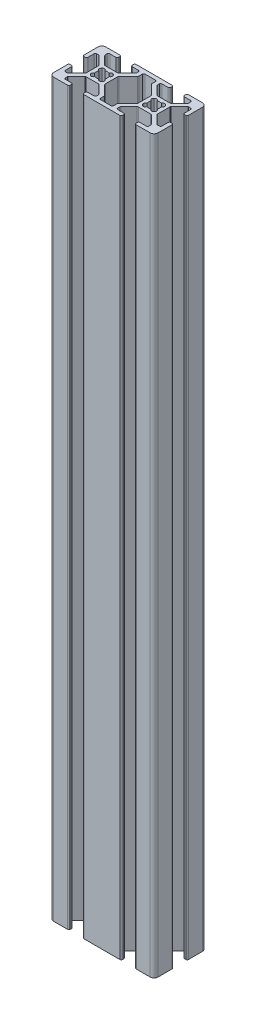
SolidWorks part; units mm, degrees
ref_plane "前视基准面" through (0, 0, 0) normal (0, 0, 1) x (1, 0, 0)
ref_plane "上视基准面" through (0, 0, 0) normal (0, 1, 0) x (1, 0, 0)
ref_plane "右视基准面" through (0, 0, 0) normal (1, 0, 0) x (0, 0, -1)
other "Configuration Table"
sketch "草图1" plane through (0, 0, 0) normal (0, 1, 0) x (1, 0, 0)
  line L0 (17.2471, 7.2074) -> (17.0675, 7.387)
  line L5 (17.0675, 11.6368) -> (17.2471, 11.8164)
  line L6 (21.4969, 11.8164) -> (21.6765, 11.6368)
  line L7 (21.6765, 7.387) -> (21.4969, 7.2074)
  line L8 (6.867, 1.5199) -> (6.867, 2.8671)
  line L9 (6.7182, 3.2263) -> (3.1758, 6.7687)
  line L10 (3.027, 7.128) -> (3.027, 11.8958)
  line L11 (3.1758, 12.255) -> (6.7182, 15.7974)
  line L26 (6.867, 16.1566) -> (6.867, 17.5039)
  line L41 (7.375, 18.0119) -> (11.369, 18.0119)
  line L56 (11.877, 17.5039) -> (11.877, 16.1566)
  line L71 (12.0258, 15.7974) -> (15.5682, 12.255)
  line L72 (15.717, 11.8958) -> (15.717, 7.128)
  line L73 (15.5682, 6.7687) -> (12.0258, 3.2263)
  line L74 (11.877, 2.8671) -> (11.877, 1.5199)
  line L75 (11.369, 1.0119) -> (7.375, 1.0119)
  line L76 (-2.7529, 7.2074) -> (-2.9325, 7.387)
  line L77 (-2.9325, 11.6368) -> (-2.7529, 11.8164)
  line L78 (1.4969, 11.8164) -> (1.6765, 11.6368)
  line L79 (1.6765, 7.387) -> (1.4969, 7.2074)
  line L80 (-3.0119, 5.8569) -> (1.7559, 5.8569)
  line L81 (2.1151, 5.7081) -> (5.2182, 2.605)
  line L82 (5.367, 2.2458) -> (5.367, 1.5199)
  line L83 (4.859, 1.0119) -> (2.51, 1.0119)
  line L84 (2.002, 0.5039) -> (2.002, 0.0199)
  line L85 (2.51, -0.4881) -> (16.234, -0.4881)
  line L86 (16.742, 0.0199) -> (16.742, 0.5039)
  line L87 (16.234, 1.0119) -> (13.885, 1.0119)
  line L88 (13.377, 1.5199) -> (13.377, 2.2458)
  line L89 (13.5258, 2.605) -> (16.6289, 5.7081)
  line L90 (16.9881, 5.8569) -> (21.7559, 5.8569)
  line L91 (22.1151, 5.7081) -> (25.2182, 2.605)
  line L92 (25.367, 2.2458) -> (25.367, 1.5199)
  line L93 (24.859, 1.0119) -> (22.51, 1.0119)
  line L94 (22.002, 0.5039) -> (22.002, 0.0199)
  line L95 (22.51, -0.4881) -> (27.872, -0.4881)
  line L96 (29.372, 1.0119) -> (29.372, 6.3739)
  line L97 (28.864, 6.8819) -> (28.38, 6.8819)
  line L98 (27.872, 6.3739) -> (27.872, 4.0249)
  line L99 (27.364, 3.5169) -> (26.6381, 3.5169)
  line L100 (26.2789, 3.6657) -> (23.1758, 6.7687)
  line L101 (23.027, 7.128) -> (23.027, 11.8958)
  line L102 (23.1758, 12.255) -> (26.2789, 15.3581)
  line L103 (26.6381, 15.5069) -> (27.364, 15.5069)
  line L104 (27.872, 14.9989) -> (27.872, 12.6499)
  line L105 (28.38, 12.1419) -> (28.864, 12.1419)
  line L106 (29.372, 12.6499) -> (29.372, 18.0119)
  line L107 (27.872, 19.5119) -> (22.51, 19.5119)
  line L108 (22.002, 19.0039) -> (22.002, 18.5199)
  line L109 (22.51, 18.0119) -> (24.859, 18.0119)
  line L110 (25.367, 17.5039) -> (25.367, 16.778)
  line L111 (25.2182, 16.4187) -> (22.1151, 13.3157)
  line L112 (21.7559, 13.1669) -> (16.9881, 13.1669)
  line L113 (16.6289, 13.3157) -> (13.5258, 16.4187)
  line L114 (13.377, 16.778) -> (13.377, 17.5039)
  line L115 (13.885, 18.0119) -> (16.234, 18.0119)
  line L116 (16.742, 18.5199) -> (16.742, 19.0039)
  line L117 (16.234, 19.5119) -> (2.51, 19.5119)
  line L118 (2.002, 19.0039) -> (2.002, 18.5199)
  line L119 (2.51, 18.0119) -> (4.859, 18.0119)
  line L120 (5.367, 17.5039) -> (5.367, 16.778)
  line L121 (5.2182, 16.4187) -> (2.1151, 13.3157)
  line L122 (1.7559, 13.1669) -> (-3.0119, 13.1669)
  line L123 (-3.3711, 13.3157) -> (-6.4742, 16.4187)
  line L124 (-6.623, 16.778) -> (-6.623, 17.5039)
  line L125 (-6.115, 18.0119) -> (-3.766, 18.0119)
  line L126 (-3.258, 18.5199) -> (-3.258, 19.0039)
  line L127 (-3.766, 19.5119) -> (-9.128, 19.5119)
  line L128 (-10.628, 18.0119) -> (-10.628, 12.6499)
  line L129 (-10.12, 12.1419) -> (-9.636, 12.1419)
  line L130 (-9.128, 12.6499) -> (-9.128, 14.9989)
  line L131 (-8.62, 15.5069) -> (-7.8941, 15.5069)
  line L132 (-7.5349, 15.3581) -> (-4.4318, 12.255)
  line L133 (-4.283, 11.8958) -> (-4.283, 7.128)
  line L134 (-4.4318, 6.7687) -> (-7.5349, 3.6657)
  line L135 (-7.8941, 3.5169) -> (-8.62, 3.5169)
  line L136 (-9.128, 4.0249) -> (-9.128, 6.3739)
  line L137 (-9.636, 6.8819) -> (-10.12, 6.8819)
  line L138 (-10.628, 6.3739) -> (-10.628, 1.0119)
  line L139 (-9.128, -0.4881) -> (-3.766, -0.4881)
  line L140 (-3.258, 0.0199) -> (-3.258, 0.5039)
  line L141 (-3.766, 1.0119) -> (-6.115, 1.0119)
  line L142 (-6.623, 1.5199) -> (-6.623, 2.2458)
  line L143 (-6.4742, 2.605) -> (-3.3711, 5.7081)
  arc A5 (17.4369, 8.7079) -> (17.0675, 7.387) centre (17.624, 7.9435) ccw
  arc A6 (17.4369, 10.3158) -> (17.4369, 8.7079) centre (19.372, 9.5119) ccw
  arc A7 (17.0675, 11.6368) -> (17.4369, 10.3158) centre (17.624, 11.0803) ccw
  arc A8 (18.568, 11.447) -> (17.2471, 11.8164) centre (17.8036, 11.2599) ccw
  arc A9 (20.176, 11.447) -> (18.568, 11.447) centre (19.372, 9.5119) ccw
  arc A10 (21.4969, 11.8164) -> (20.176, 11.447) centre (20.9404, 11.2599) ccw
  arc A11 (21.3071, 10.3158) -> (21.6765, 11.6368) centre (21.12, 11.0803) ccw
  arc A12 (21.3071, 8.7079) -> (21.3071, 10.3158) centre (19.372, 9.5119) ccw
  arc A13 (21.6765, 7.387) -> (21.3071, 8.7079) centre (21.12, 7.9435) ccw
  arc A14 (20.176, 7.5767) -> (21.4969, 7.2074) centre (20.9404, 7.7639) ccw
  arc A15 (18.568, 7.5767) -> (20.176, 7.5767) centre (19.372, 9.5119) ccw
  arc A16 (17.2471, 7.2074) -> (18.568, 7.5767) centre (17.8036, 7.7639) ccw
  arc A17 (6.867, 1.5199) -> (7.375, 1.0119) centre (7.375, 1.5199) ccw
  arc A18 (6.867, 2.8671) -> (6.7182, 3.2263) centre (6.359, 2.8671) ccw
  arc A19 (3.027, 7.128) -> (3.1758, 6.7687) centre (3.535, 7.128) ccw
  arc A20 (3.1758, 12.255) -> (3.027, 11.8958) centre (3.535, 11.8958) ccw
  arc A21 (6.7182, 15.7974) -> (6.867, 16.1566) centre (6.359, 16.1566) ccw
  arc A22 (7.375, 18.0119) -> (6.867, 17.5039) centre (7.375, 17.5039) ccw
  arc A23 (11.877, 17.5039) -> (11.369, 18.0119) centre (11.369, 17.5039) ccw
  arc A24 (11.877, 16.1566) -> (12.0258, 15.7974) centre (12.385, 16.1566) ccw
  arc A25 (15.717, 11.8958) -> (15.5682, 12.255) centre (15.209, 11.8958) ccw
  arc A26 (15.5682, 6.7687) -> (15.717, 7.128) centre (15.209, 7.128) ccw
  arc A27 (12.0258, 3.2263) -> (11.877, 2.8671) centre (12.385, 2.8671) ccw
  arc A28 (11.369, 1.0119) -> (11.877, 1.5199) centre (11.369, 1.5199) ccw
  arc A29 (-2.5631, 8.7079) -> (-2.9325, 7.387) centre (-2.376, 7.9435) ccw
  arc A30 (-2.5631, 10.3158) -> (-2.5631, 8.7079) centre (-0.628, 9.5119) ccw
  arc A31 (-2.9325, 11.6368) -> (-2.5631, 10.3158) centre (-2.376, 11.0803) ccw
  arc A32 (-1.432, 11.447) -> (-2.7529, 11.8164) centre (-2.1964, 11.2599) ccw
  arc A33 (0.176, 11.447) -> (-1.432, 11.447) centre (-0.628, 9.5119) ccw
  arc A34 (1.4969, 11.8164) -> (0.176, 11.447) centre (0.9404, 11.2599) ccw
  arc A35 (1.3071, 10.3158) -> (1.6765, 11.6368) centre (1.12, 11.0803) ccw
  arc A36 (1.3071, 8.7079) -> (1.3071, 10.3158) centre (-0.628, 9.5119) ccw
  arc A37 (1.6765, 7.387) -> (1.3071, 8.7079) centre (1.12, 7.9435) ccw
  arc A38 (0.176, 7.5767) -> (1.4969, 7.2074) centre (0.9404, 7.7639) ccw
  arc A39 (-1.432, 7.5767) -> (0.176, 7.5767) centre (-0.628, 9.5119) ccw
  arc A40 (-2.7529, 7.2074) -> (-1.432, 7.5767) centre (-2.1964, 7.7639) ccw
  arc A41 (-3.0119, 5.8569) -> (-3.3711, 5.7081) centre (-3.0119, 5.3489) ccw
  arc A42 (2.1151, 5.7081) -> (1.7559, 5.8569) centre (1.7559, 5.3489) ccw
  arc A43 (5.367, 2.2458) -> (5.2182, 2.605) centre (4.859, 2.2458) ccw
  arc A44 (4.859, 1.0119) -> (5.367, 1.5199) centre (4.859, 1.5199) ccw
  arc A45 (2.51, 1.0119) -> (2.002, 0.5039) centre (2.51, 0.5039) ccw
  arc A46 (2.002, 0.0199) -> (2.51, -0.4881) centre (2.51, 0.0199) ccw
  arc A47 (16.234, -0.4881) -> (16.742, 0.0199) centre (16.234, 0.0199) ccw
  arc A48 (16.742, 0.5039) -> (16.234, 1.0119) centre (16.234, 0.5039) ccw
  arc A49 (13.377, 1.5199) -> (13.885, 1.0119) centre (13.885, 1.5199) ccw
  arc A50 (13.5258, 2.605) -> (13.377, 2.2458) centre (13.885, 2.2458) ccw
  arc A51 (16.9881, 5.8569) -> (16.6289, 5.7081) centre (16.9881, 5.3489) ccw
  arc A52 (22.1151, 5.7081) -> (21.7559, 5.8569) centre (21.7559, 5.3489) ccw
  arc A53 (25.367, 2.2458) -> (25.2182, 2.605) centre (24.859, 2.2458) ccw
  arc A54 (24.859, 1.0119) -> (25.367, 1.5199) centre (24.859, 1.5199) ccw
  arc A55 (22.51, 1.0119) -> (22.002, 0.5039) centre (22.51, 0.5039) ccw
  arc A56 (22.002, 0.0199) -> (22.51, -0.4881) centre (22.51, 0.0199) ccw
  arc A57 (27.872, -0.4881) -> (29.372, 1.0119) centre (27.872, 1.0119) ccw
  arc A58 (29.372, 6.3739) -> (28.864, 6.8819) centre (28.864, 6.3739) ccw
  arc A59 (28.38, 6.8819) -> (27.872, 6.3739) centre (28.38, 6.3739) ccw
  arc A60 (27.364, 3.5169) -> (27.872, 4.0249) centre (27.364, 4.0249) ccw
  arc A61 (26.2789, 3.6657) -> (26.6381, 3.5169) centre (26.6381, 4.0249) ccw
  arc A62 (23.027, 7.128) -> (23.1758, 6.7687) centre (23.535, 7.128) ccw
  arc A63 (23.1758, 12.255) -> (23.027, 11.8958) centre (23.535, 11.8958) ccw
  arc A64 (26.6381, 15.5069) -> (26.2789, 15.3581) centre (26.6381, 14.9989) ccw
  arc A65 (27.872, 14.9989) -> (27.364, 15.5069) centre (27.364, 14.9989) ccw
  arc A66 (27.872, 12.6499) -> (28.38, 12.1419) centre (28.38, 12.6499) ccw
  arc A67 (28.864, 12.1419) -> (29.372, 12.6499) centre (28.864, 12.6499) ccw
  arc A68 (29.372, 18.0119) -> (27.872, 19.5119) centre (27.872, 18.0119) ccw
  arc A69 (22.51, 19.5119) -> (22.002, 19.0039) centre (22.51, 19.0039) ccw
  arc A70 (22.002, 18.5199) -> (22.51, 18.0119) centre (22.51, 18.5199) ccw
  arc A71 (25.367, 17.5039) -> (24.859, 18.0119) centre (24.859, 17.5039) ccw
  arc A72 (25.2182, 16.4187) -> (25.367, 16.778) centre (24.859, 16.778) ccw
  arc A73 (21.7559, 13.1669) -> (22.1151, 13.3157) centre (21.7559, 13.6749) ccw
  arc A74 (16.6289, 13.3157) -> (16.9881, 13.1669) centre (16.9881, 13.6749) ccw
  arc A75 (13.377, 16.778) -> (13.5258, 16.4187) centre (13.885, 16.778) ccw
  arc A76 (13.885, 18.0119) -> (13.377, 17.5039) centre (13.885, 17.5039) ccw
  arc A77 (16.234, 18.0119) -> (16.742, 18.5199) centre (16.234, 18.5199) ccw
  arc A78 (16.742, 19.0039) -> (16.234, 19.5119) centre (16.234, 19.0039) ccw
  arc A79 (2.51, 19.5119) -> (2.002, 19.0039) centre (2.51, 19.0039) ccw
  arc A80 (2.002, 18.5199) -> (2.51, 18.0119) centre (2.51, 18.5199) ccw
  arc A81 (5.367, 17.5039) -> (4.859, 18.0119) centre (4.859, 17.5039) ccw
  arc A82 (5.2182, 16.4187) -> (5.367, 16.778) centre (4.859, 16.778) ccw
  arc A83 (1.7559, 13.1669) -> (2.1151, 13.3157) centre (1.7559, 13.6749) ccw
  arc A84 (-3.3711, 13.3157) -> (-3.0119, 13.1669) centre (-3.0119, 13.6749) ccw
  arc A85 (-6.623, 16.778) -> (-6.4742, 16.4187) centre (-6.115, 16.778) ccw
  arc A86 (-6.115, 18.0119) -> (-6.623, 17.5039) centre (-6.115, 17.5039) ccw
  arc A87 (-3.766, 18.0119) -> (-3.258, 18.5199) centre (-3.766, 18.5199) ccw
  arc A88 (-3.258, 19.0039) -> (-3.766, 19.5119) centre (-3.766, 19.0039) ccw
  arc A89 (-9.128, 19.5119) -> (-10.628, 18.0119) centre (-9.128, 18.0119) ccw
  arc A90 (-10.628, 12.6499) -> (-10.12, 12.1419) centre (-10.12, 12.6499) ccw
  arc A91 (-9.636, 12.1419) -> (-9.128, 12.6499) centre (-9.636, 12.6499) ccw
  arc A92 (-8.62, 15.5069) -> (-9.128, 14.9989) centre (-8.62, 14.9989) ccw
  arc A93 (-7.5349, 15.3581) -> (-7.8941, 15.5069) centre (-7.8941, 14.9989) ccw
  arc A94 (-4.283, 11.8958) -> (-4.4318, 12.255) centre (-4.791, 11.8958) ccw
  arc A95 (-4.4318, 6.7687) -> (-4.283, 7.128) centre (-4.791, 7.128) ccw
  arc A96 (-7.8941, 3.5169) -> (-7.5349, 3.6657) centre (-7.8941, 4.0249) ccw
  arc A97 (-9.128, 4.0249) -> (-8.62, 3.5169) centre (-8.62, 4.0249) ccw
  arc A98 (-9.128, 6.3739) -> (-9.636, 6.8819) centre (-9.636, 6.3739) ccw
  arc A99 (-10.12, 6.8819) -> (-10.628, 6.3739) centre (-10.12, 6.3739) ccw
  arc A100 (-10.628, 1.0119) -> (-9.128, -0.4881) centre (-9.128, 1.0119) ccw
  arc A101 (-3.766, -0.4881) -> (-3.258, 0.0199) centre (-3.766, 0.0199) ccw
  arc A102 (-3.258, 0.5039) -> (-3.766, 1.0119) centre (-3.766, 0.5039) ccw
  arc A103 (-6.623, 1.5199) -> (-6.115, 1.0119) centre (-6.115, 1.5199) ccw
  arc A104 (-6.4742, 2.605) -> (-6.623, 2.2458) centre (-6.115, 2.2458) ccw
extrude "凸台-拉伸1" add sketch "草图1" along normal mid plane 280
